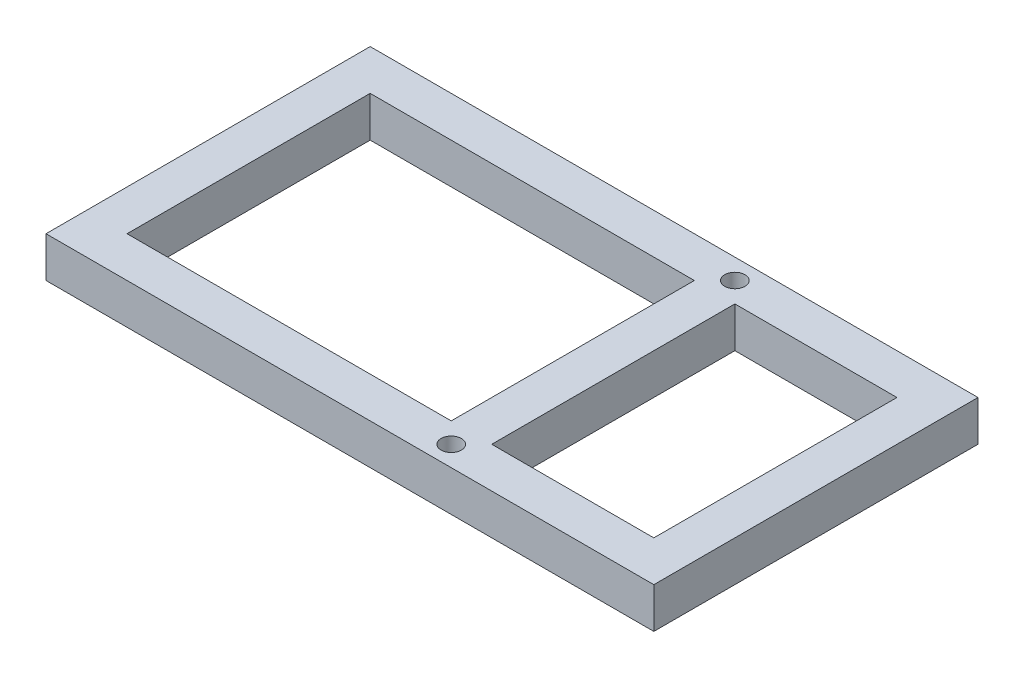
SolidWorks part; units mm, degrees
material "6061 Alloy"
ref_plane "Front Plane" through (0, 0, 0) normal (0, 0, 1) x (1, 0, 0)
ref_plane "Top Plane" through (0, 0, 0) normal (0, 1, 0) x (1, 0, 0)
ref_plane "Right Plane" through (0, 0, 0) normal (1, 0, 0) x (0, 0, -1)
sketch "Sketch1" plane through (0, 0, 0) normal (0, 1, 0) x (1, 0, 0)
  line L1 (-75, 40) -> (75, 40)
  line L2 (-75, 40) -> (-75, -40)
  line L3 (-75, -40) -> (75, -40)
  line L4 (75, 40) -> (75, -40)
  line L5 (-75, 40) -> (75, -40) construction
  line L6 (-75, -40) -> (75, 40) construction
  point P0 (0, 0)
  point P6 (0, 0)
  dimension "D1" = 150
  dimension "D2" = 80
extrude "Boss-Extrude1" add sketch "Sketch1" against normal blind 10
sketch "Sketch2" plane through (0, 0, 0) normal (0, 1, 0) x (1, 0, 0)
  line L0 (-75, 40) -> (-75, -40) construction
  line L1 (-65, 30) -> (15, 30)
  line L2 (-65, 30) -> (-65, -30)
  line L3 (-65, -30) -> (15, -30)
  line L4 (15, 30) -> (15, -30)
  line L5 (-65, 30) -> (15, -30) construction
  line L6 (-65, -30) -> (15, 30) construction
  line L7 (65, 30) -> (25, 30)
  line L8 (65, 30) -> (65, -30)
  line L9 (65, -30) -> (25, -30)
  line L10 (25, 30) -> (25, -30)
  line L11 (65, 30) -> (25, -30) construction
  line L12 (65, -30) -> (25, 30) construction
  line L13 (75, -40) -> (75, 40) construction
  point P0 (-25, 0)
  point P5 (45, 0)
  point P12 (-75, 0)
  dimension "D1" = 60
  dimension "D2" = 80
  dimension "D3" = 10
  dimension "D4" = 10
  dimension "D5" = 10
extrude "Cut-Extrude1" cut sketch "Sketch2" against normal blind 10
sketch "Sketch3" plane through (0, 0, 0) normal (0, 1, 0) x (1, 0, 0)
  line L1 (15, -30) -> (15, 30) construction
  line L2 (15, 0) -> (25, 0) construction
  line L3 (25, 30) -> (25, -30) construction
  line L4 (15, 30) -> (15, 40) construction
  line L5 (75, 40) -> (-75, 40) construction
  circle A0 centre (20, 35) radius 2.5
  circle A1 centre (20, -35) radius 2.5
  point P13 (15, 35)
  point P14 (20, 0)
  dimension "D1" = 5
extrude "Cut-Extrude2" cut sketch "Sketch3" against normal through all
